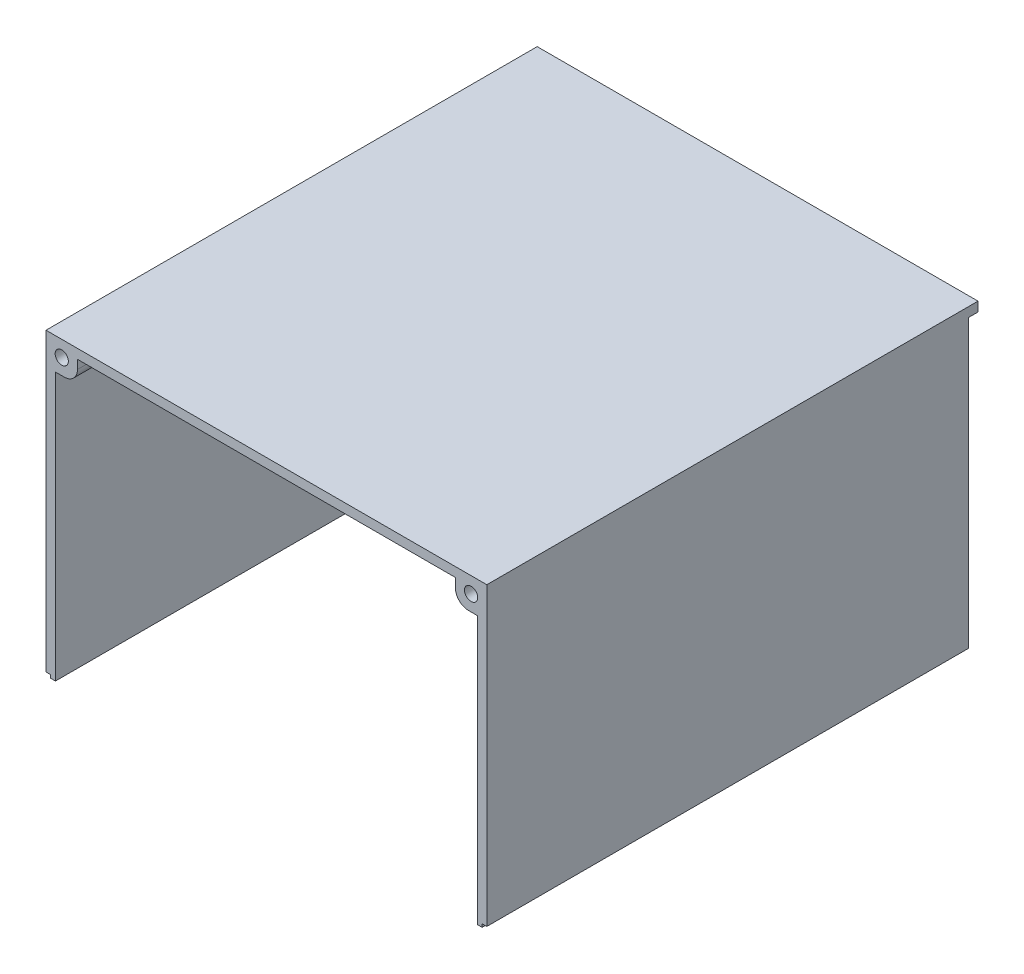
SolidWorks part; units mm, degrees
material "ABS"
ref_plane "Спереди" through (0, 0, 0) normal (0, 0, 1) x (1, 0, 0)
ref_plane "Сверху" through (0, 0, 0) normal (0, 1, 0) x (1, 0, 0)
ref_plane "Справа" through (0, 0, 0) normal (1, 0, 0) x (0, 0, -1)
sketch "Эскиз1" plane through (0, 0, 0) normal (0, 0, 1) x (1, 0, 0)
  line L0 (-70, 1) -> (-70, 95)
  line L1 (-70, 95) -> (70, 95)
  line L7 (67, 92) -> (-67, 92)
  line L8 (-67, 92) -> (-67, 0)
  line L9 (-67, 0) -> (-68.5, 0)
  line L10 (-68.5, 0) -> (-68.5, 1)
  line L11 (-68.5, 1) -> (-70, 1)
  line L12 (0, -62.6292) -> (0, 88.9043) construction
  line L13 (68.5, 1) -> (70, 1)
  line L14 (68.5, 0) -> (68.5, 1)
  line L15 (67, 0) -> (68.5, 0)
  line L16 (67, 92) -> (67, 0)
  line L17 (70, 1) -> (70, 95)
  point P14 (0, 95)
  point P18 (0, 92)
  dimension "D1" = 94
  dimension "D2" = 1.5
  dimension "D3" = 1.5
  dimension "D4" = 1
  dimension "D5" = 3
  dimension "D6" = 140
extrude "Бобышка-Вытянуть1" add sketch "Эскиз1" along normal blind 153
sketch "Эскиз2" plane through (0, 0, 0) normal (0, 0, -1) x (-1, 0, 0)
  line L2 (-70, 1) -> (-70, 95) construction
  line L3 (-70, 92) -> (-70, 95)
  line L4 (-70, 95) -> (70, 95)
  line L5 (-70, 95) -> (70, 95) construction
  line L6 (70, 95) -> (70, 1) construction
  line L7 (70, 95) -> (70, 93)
  line L11 (-70, 92) -> (-67, 92)
  line L12 (-67, 92) -> (-67, 93)
  line L13 (-67, 93) -> (67, 93)
  line L14 (67, 93) -> (67, 92)
  line L15 (67, 92) -> (70, 92)
  line L16 (70, 92) -> (70, 93)
  line L18 (67, 92) -> (-67, 92) construction
  dimension "D1" = 1
extrude "Бобышка-Вытянуть2" add sketch "Эскиз2" along normal blind 1.5 contours L13 L14 L15 L16 L7 L4 L3 L11 L12
sketch "Эскиз3" plane through (0, 0, -1.5) normal (0, 0, -1) x (-1, 0, 0)
  line L1 (-70, 92) -> (70, 92)
  line L2 (-70, 92) -> (-70, 95)
  line L3 (-70, 95) -> (70, 95)
  line L4 (70, 92) -> (70, 95)
extrude "Бобышка-Вытянуть3" add sketch "Эскиз3" along normal blind 1.5
sketch "Эскиз4" plane through (0, 0, 153) normal (0, 0, 1) x (1, 0, 0)
  line L0 (0, -7.5391) -> (0, 119.4766) construction
  line L1 (-67, 92) -> (-60, 92)
  line L2 (-67, 92) -> (-67, 85)
  line L3 (-67, 85) -> (-64.2, 85)
  line L4 (-60, 92) -> (-60, 89.2)
  line L5 (60, 92) -> (60, 89.2)
  line L6 (67, 85) -> (64.2, 85)
  line L7 (67, 92) -> (67, 85)
  line L8 (67, 92) -> (60, 92)
  line L9 (-70, 95) -> (-70, 1) construction
  line L10 (70, 95) -> (-70, 95) construction
  circle A0 centre (-65, 90) radius 2.1 construction
  arc A1 (-64.2, 85) -> (-60, 89.2) centre (-64.2, 89.2) ccw
  arc A2 (60, 89.2) -> (64.2, 85) centre (64.2, 89.2) ccw
  point P20 (-60, 85)
  point P23 (60, 85)
  point P24 (0, 0)
  dimension "D3" = 4.2
  dimension "D4" = 5
  dimension "D5" = 5
  dimension "D6" = 4.2
  dimension "D7" = 4.2
  dimension "D1" = 5
  dimension "D2" = 5
extrude "Бобышка-Вытянуть4" add sketch "Эскиз4" against normal blind 8
sketch "Эскиз5" plane through (0, 0, 153) normal (0, 0, 1) x (1, 0, 0)
  line L0 (-70, 95) -> (-70, 1) construction
  line L1 (70, 95) -> (-70, 95) construction
  line L2 (0, 0) -> (0, 140.8618) construction
  circle A0 centre (-65, 90) radius 2.1
  circle A1 centre (65, 90) radius 2.1
  dimension "D1" = 4.2
  dimension "D2" = 5
  dimension "D3" = 5
extrude "Вырез-Вытянуть1" cut sketch "Эскиз5" against normal blind 4.2
